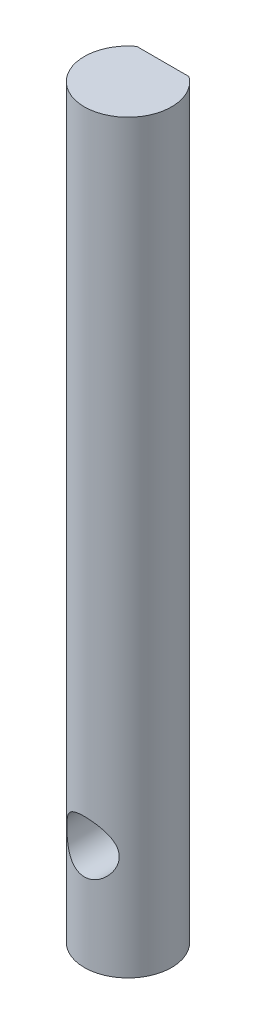
SolidWorks part; units mm, degrees
ref_plane "Front Plane" through (0, 0, 0) normal (0, 0, 1) x (1, 0, 0)
ref_plane "Top Plane" through (0, 0, 0) normal (0, 1, 0) x (1, 0, 0)
ref_plane "Right Plane" through (0, 0, 0) normal (1, 0, 0) x (0, 0, -1)
sketch "Sketch1" plane through (0, 0, 0) normal (0, 1, 0) x (1, 0, 0)
  line L0 (-1.5, 2) -> (1.5, 2)
  circle A0 centre (0, 0) radius 2.5
  point P5 (0, 0)
  point P6 (-0.8874, 2)
  dimension "D1" = 5
  dimension "D2" = 2
extrude "Boss-Extrude1" add sketch "Sketch1" along normal blind 42.7 contours L0 A0
sketch "Sketch2" plane through (0, 0, -2) normal (0, 0, -1) x (-1, 0, 0)
  circle A0 centre (0, 6) radius 1.5
  point P2 (0.4017, 5.9865)
  point P4 (0, 0)
  dimension "D2" = 3
  dimension "D1" = 6
extrude "Cut-Extrude1" cut sketch "Sketch2" against normal through all both and the other way through all
